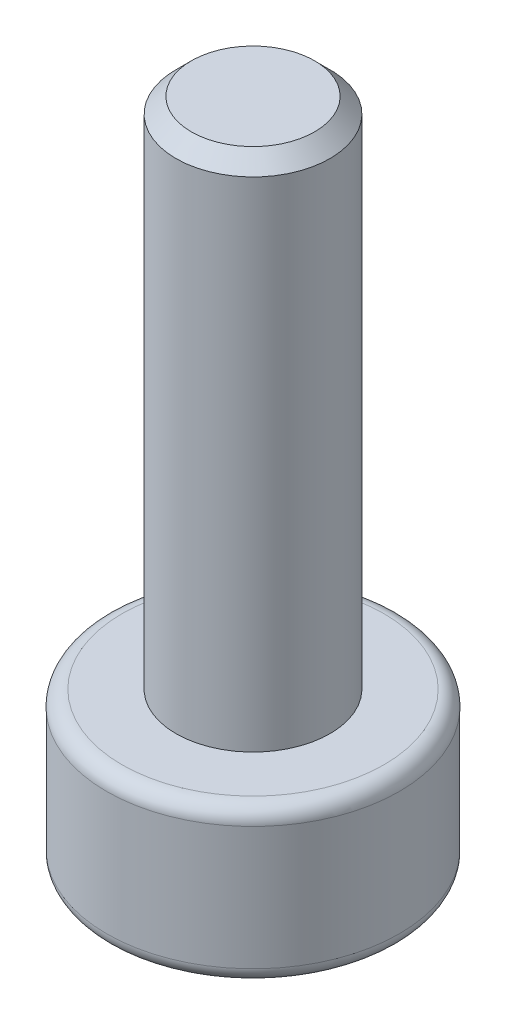
SolidWorks part; units mm, degrees
material "AISI 304"
ref_plane "前视基准面" through (0, 0, 0) normal (0, 0, 1) x (1, 0, 0)
ref_plane "上视基准面" through (0, 0, 0) normal (0, 1, 0) x (1, 0, 0)
ref_plane "右视基准面" through (0, 0, 0) normal (1, 0, 0) x (0, 0, -1)
sketch "草图1" plane through (0, 0, 0) normal (0, 1, 0) x (1, 0, 0)
  circle A0 centre (0, 0) radius 2.85
  dimension "D1" = 5.7
extrude "凸台-拉伸1" add sketch "草图1" along normal blind 3
sketch "草图2" plane through (0, 3, 0) normal (0, 1, 0) x (1, 0, 0)
  circle A0 centre (0, 0) radius 1.5
  dimension "D1" = 3
extrude "凸台-拉伸2" add sketch "草图2" along normal blind 10
sketch "草图3" plane through (0, 0, 0) normal (0, -1, 0) x (1, 0, 0)
  circle A0 centre (0, 0) radius 1.29
  dimension "D1" = 2.58
extrude "切除-拉伸1" cut sketch "草图3" against normal blind 1.3
fillet "圆角1" radius 0.3 2 edges at (0, 3, 2.85) (0, 0, 2.85)
chamfer "倒角1" distance 0.3 angle 45 1 edges at (0, 13, 1.5)
chamfer "倒角2" distance 0.15 angle 45 1 edges at (0, 0, -1.29)
